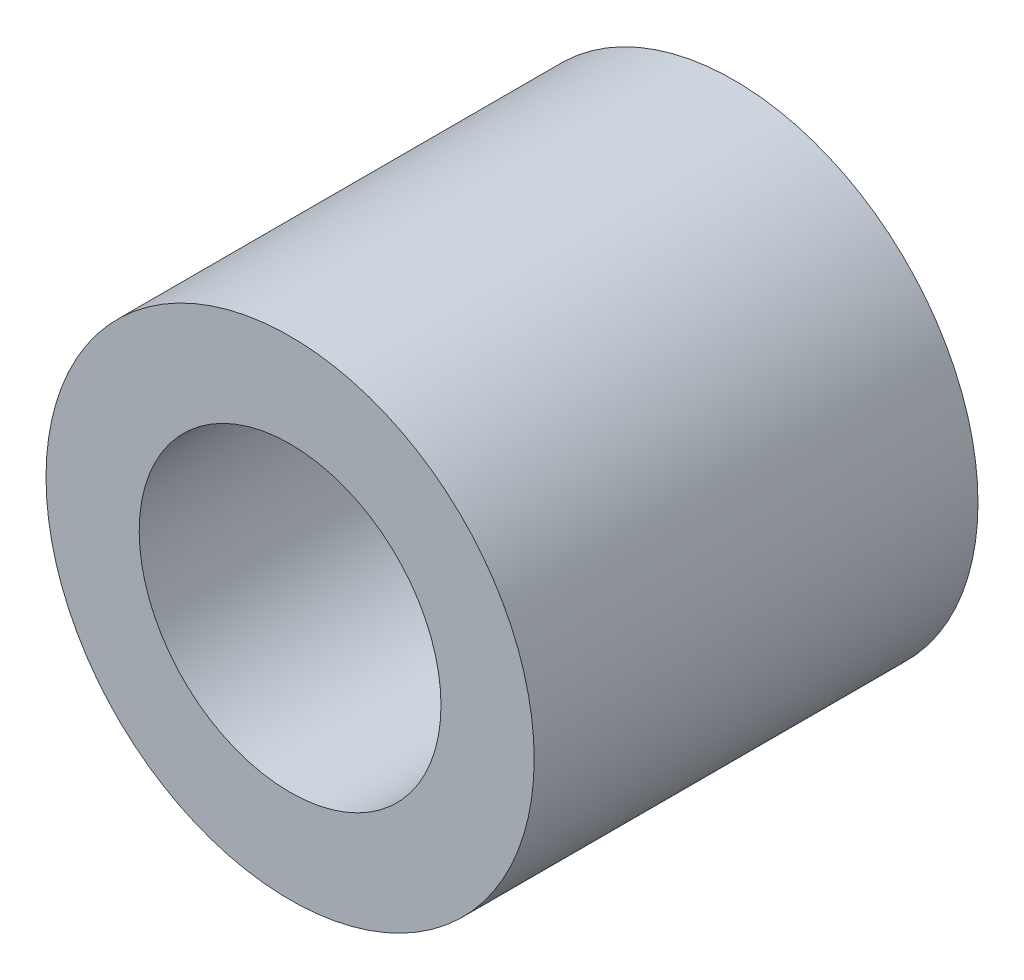
SolidWorks part; units mm, degrees
material "ABS"
ref_plane "前视基准面" through (0, 0, 0) normal (0, 0, 1) x (1, 0, 0)
ref_plane "上视基准面" through (0, 0, 0) normal (0, 1, 0) x (1, 0, 0)
ref_plane "右视基准面" through (0, 0, 0) normal (1, 0, 0) x (0, 0, -1)
sketch "草图1" plane through (0, 0, 0) normal (0, 0, 1) x (1, 0, 0)
  circle A0 centre (0, 0) radius 1.7
  circle A1 centre (0, 0) radius 2.75
  dimension "D1" = 5.5
  dimension "D2" = 3.4
extrude "凸台-拉伸1" add sketch "草图1" along normal blind 5
